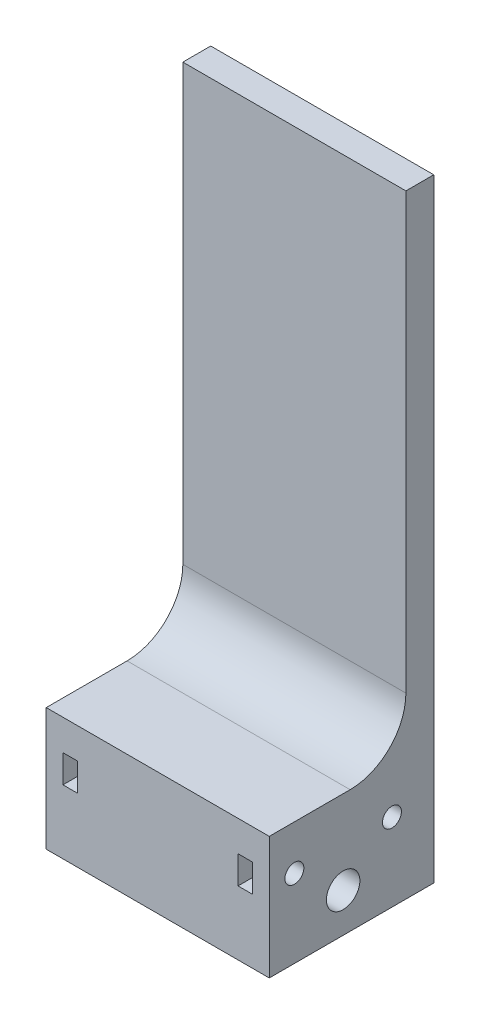
SolidWorks part; units mm, degrees
ref_plane "Front Plane" through (0, 0, 0) normal (0, 0, 1) x (1, 0, 0)
ref_plane "Top Plane" through (0, 0, 0) normal (0, 1, 0) x (1, 0, 0)
ref_plane "Right Plane" through (0, 0, 0) normal (1, 0, 0) x (0, 0, -1)
sketch "Sketch1" plane through (20, 0, 0) normal (-1, 0, 0) x (0, 0, 1)
  line L0 (-22.5, 37) -> (-22.5, 5) construction
  line L1 (2, 17) -> (-27.5, 17)
  line L2 (2, 17) -> (2, 39)
  line L3 (-22.5, 127) -> (-27.5, 127)
  line L4 (-27.5, 17) -> (-27.5, 127)
  line L5 (0, 5) -> (0, 37) construction
  line L6 (0, 37) -> (-22.5, 37) construction
  line L7 (-2.5, 31) -> (-20, 31) construction
  line L10 (2, 39) -> (-22.5, 39)
  line L11 (-22.5, 127) -> (-22.5, 39)
  circle A6 centre (-11.25, 24) radius 3
  circle A7 centre (-2.5, 31) radius 1.7
  circle A8 centre (-20, 31) radius 1.7
  point P2 (-11.25, 31)
  point P5 (0, 0)
  point P7 (-11.25, 24)
  dimension "D4" = 3.4
  dimension "D5" = 6
  dimension "D1" = 5
  dimension "D2" = 2
  dimension "D3" = 20
  dimension "D6" = 110
  dimension "D7" = 2
  dimension "D8" = 5
  dimension "D9" = 17.5
  dimension "D10" = 7
  dimension "D11" = 8
  dimension "D12" = 4.5
extrude "Boss-Extrude1" add sketch "Sketch1" along normal up to surface (40 mm away)
fillet "Fillet1" radius 10 1 edges at (0, 39, -22.5)
sketch "Sketch2" plane through (0, 0, 2) normal (0, 0, 1) x (1, 0, 0)
  line L0 (39, 29.5) -> (39, 32.5) construction
  line L1 (39, 29.5) -> (39, 32.5) construction
  line L2 (39, 31) -> (-39, 31) construction
  line L3 (14.4, 33.5) -> (17, 33.5)
  line L4 (14.4, 33.5) -> (14.4, 28.5)
  line L5 (14.4, 28.5) -> (17, 28.5)
  line L6 (17, 33.5) -> (17, 28.5)
  line L7 (-14.4, 33.5) -> (-17, 33.5)
  line L8 (-14.4, 33.5) -> (-14.4, 28.5)
  line L9 (-14.4, 28.5) -> (-17, 28.5)
  line L10 (-17, 33.5) -> (-17, 28.5)
  line L11 (-39, 37) -> (-39, 5) construction
  line L12 (0, 31) -> (0, 0) construction
  line L13 (-20, 39) -> (-20, 17) construction
  point P15 (17, 31)
  point P16 (-14.4, 31)
  dimension "D1" = 2.6
  dimension "D2" = 5
  dimension "D3" = 3
extrude "Cut-Extrude1" cut sketch "Sketch2" against normal blind 7
sketch "Sketch3" plane through (0, 0, -27.5) normal (0, 0, -1) x (-1, 0, 0)
  line L4 (17, 33.5) -> (14.4, 33.5)
  line L5 (17, 28.5) -> (17, 33.5)
  line L6 (14.4, 28.5) -> (17, 28.5)
  line L7 (14.4, 33.5) -> (14.4, 28.5)
  line L8 (17, 33.5) -> (14.4, 33.5)
  line L9 (17, 28.5) -> (17, 33.5)
  line L10 (14.4, 28.5) -> (17, 28.5)
  line L11 (14.4, 33.5) -> (14.4, 28.5)
  line L12 (-14.4, 33.5) -> (-17, 33.5)
  line L13 (-17, 33.5) -> (-17, 28.5)
  line L14 (-17, 28.5) -> (-14.4, 28.5)
  line L15 (-14.4, 28.5) -> (-14.4, 33.5)
  line L16 (-14.4, 33.5) -> (-17, 33.5)
  line L17 (-17, 33.5) -> (-17, 28.5)
  line L18 (-17, 28.5) -> (-14.4, 28.5)
  line L19 (-14.4, 28.5) -> (-14.4, 33.5)
  dimension "D1" = 0
  dimension "D2" = 0
extrude "Cut-Extrude2" cut sketch "Sketch3" against normal blind 11
sketch "Sketch4" plane through (-20, 0, 0) normal (-1, 0, 0) x (0, 0, 1)
  line L6 (2, 39) -> (-12.5, 39)
  line L7 (-22.5, 49) -> (-22.5, 127)
  line L8 (-22.5, 127) -> (-27.5, 127)
  line L9 (-27.5, 127) -> (-27.5, 17)
  line L10 (-27.5, 17) -> (2, 17)
  line L11 (2, 17) -> (2, 39)
  line L12 (2, 39) -> (-12.5, 39)
  line L13 (-22.5, 49) -> (-22.5, 127)
  line L14 (-22.5, 127) -> (-27.5, 127)
  line L15 (-27.5, 127) -> (-27.5, 17)
  line L16 (-27.5, 17) -> (2, 17)
  line L17 (2, 17) -> (2, 39)
  arc A1 (-22.5, 49) -> (-12.5, 39) centre (-12.5, 49) ccw
  arc A2 (-22.5, 49) -> (-12.5, 39) centre (-12.5, 49) ccw
  dimension "D1" = 0
extrude "Cut-Extrude3" [suppressed] cut sketch "Sketch4" against normal blind 32
sketch "Sketch5" [suppressed] plane through (12, 0, 0) normal (-1, 0, 0) x (0, 0, 1)
  line L0 (2, 39) -> (-12.5, 39) construction
  line L1 (-27.5, 127) -> (-5.25, 127)
  line L2 (-27.5, 127) -> (-27.5, 39)
  line L3 (-27.5, 39) -> (-5.25, 39)
  line L4 (-5.25, 127) -> (-5.25, 39)
extrude "Cut-Extrude4" [suppressed] cut sketch "Sketch5" against normal blind 32
